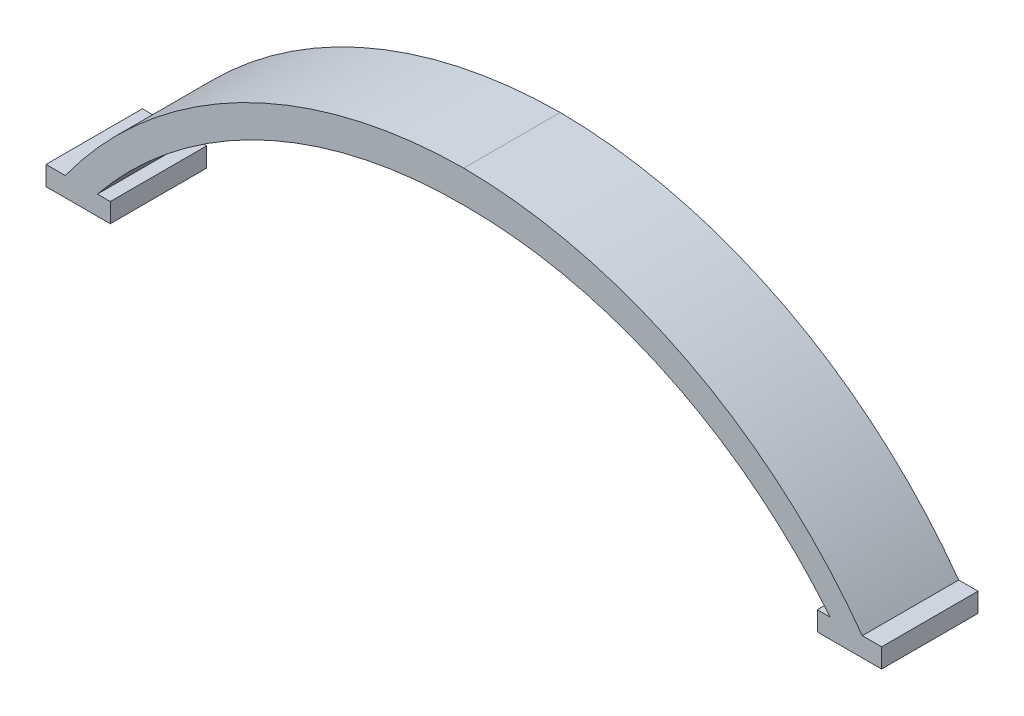
SolidWorks part; units mm, degrees
ref_plane "Front Plane" through (0, 0, 0) normal (0, 0, 1) x (1, 0, 0)
ref_plane "Top Plane" through (0, 0, 0) normal (0, 1, 0) x (1, 0, 0)
ref_plane "Right Plane" through (0, 0, 0) normal (1, 0, 0) x (0, 0, -1)
sketch "Sketch1" plane through (0, 0, 0) normal (0, 0, 1) x (1, 0, 0)
  line L0 (82.55, 0) -> (82.55, 38.1) construction
  line L1 (0, 0) -> (12.7, 0)
  line L2 (12.7, 0) -> (12.7, 3.81)
  line L3 (12.7, 3.81) -> (10.16, 3.81)
  line L4 (0, 0) -> (0, 3.81)
  line L5 (0, 3.81) -> (3.81, 3.81)
  line L7 (152.4, 3.81) -> (154.94, 3.81)
  line L8 (152.4, 0) -> (152.4, 3.81)
  line L9 (165.1, 0) -> (152.4, 0)
  line L10 (165.1, 0) -> (165.1, 3.81)
  line L11 (165.1, 3.81) -> (161.29, 3.81)
  line L12 (82.55, 44.45) -> (82.55, 50.8) construction
  arc A0 (10.16, 3.81) -> (82.55, 38.1) centre (81.9597, -54.2105) cw
  arc A1 (3.81, 3.81) -> (82.55, 44.45) centre (83.2178, -53.4433) cw
  arc A2 (154.94, 3.81) -> (82.55, 38.1) centre (83.1403, -54.2105) ccw
  arc A3 (161.29, 3.81) -> (82.55, 44.45) centre (81.8822, -53.4433) ccw
  dimension "D8" = 97.8956
  dimension "D9" = 92.3124
  dimension "D1" = 50.8
  dimension "D2" = 82.55
  dimension "D3" = 12.7
  dimension "D4" = 38.1
  dimension "D5" = 44.45
  dimension "D6" = 6.35
  dimension "D7" = 3.81
  dimension "D10" = 3.81
extrude "Boss-Extrude1" add sketch "Sketch1" along normal blind 19.05
